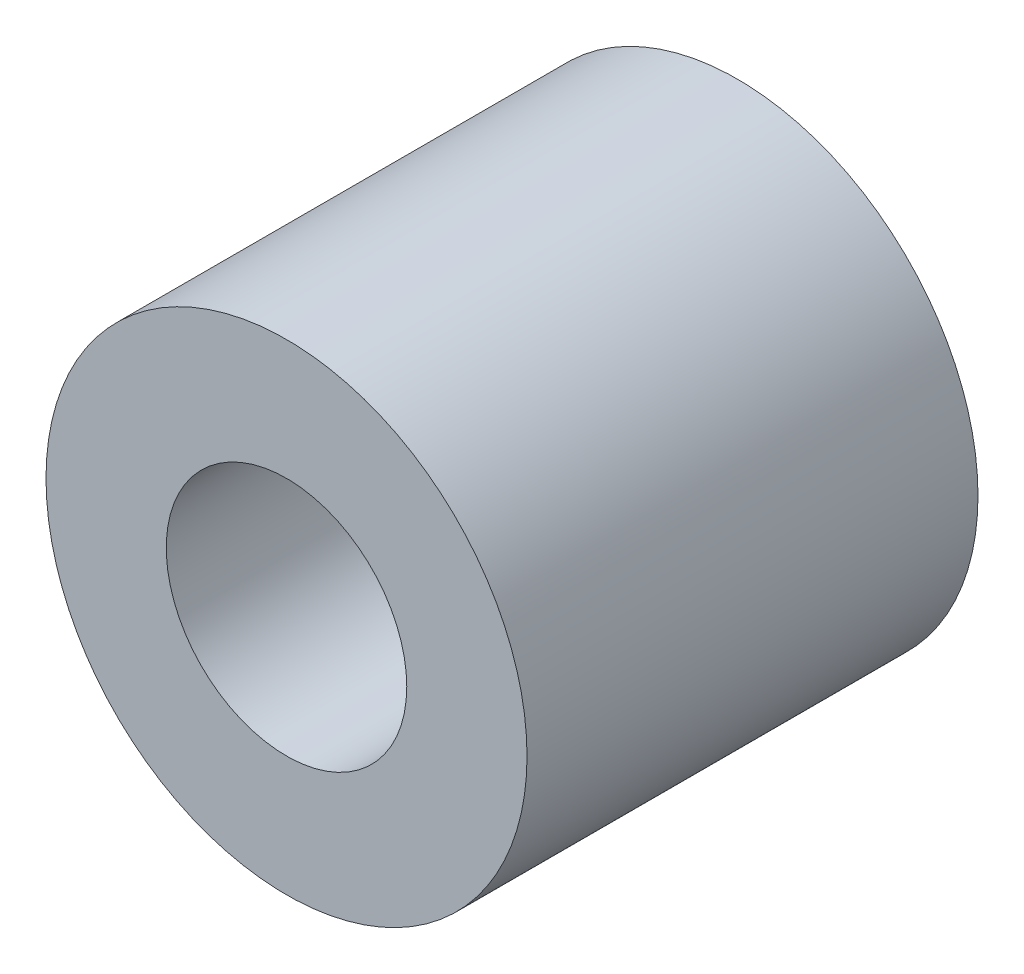
SolidWorks part; units mm, degrees
ref_plane "Front Plane" through (0, 0, 0) normal (0, 0, 1) x (1, 0, 0)
ref_plane "Top Plane" through (0, 0, 0) normal (0, 1, 0) x (1, 0, 0)
ref_plane "Right Plane" through (0, 0, 0) normal (1, 0, 0) x (0, 0, -1)
sketch "Sketch1" plane through (0, 0, 0) normal (0, 0, 1) x (1, 0, 0)
  circle A0 centre (0, 0) radius 8
  dimension "D1" = 16
extrude "Boss-Extrude1" add sketch "Sketch1" along normal blind 15
sketch "Sketch2" plane through (0, 0, 15) normal (0, 0, 1) x (1, 0, 0)
  circle A0 centre (0, 0) radius 4
  dimension "D1" = 8
extrude "Cut-Extrude1" cut sketch "Sketch2" against normal blind 14
